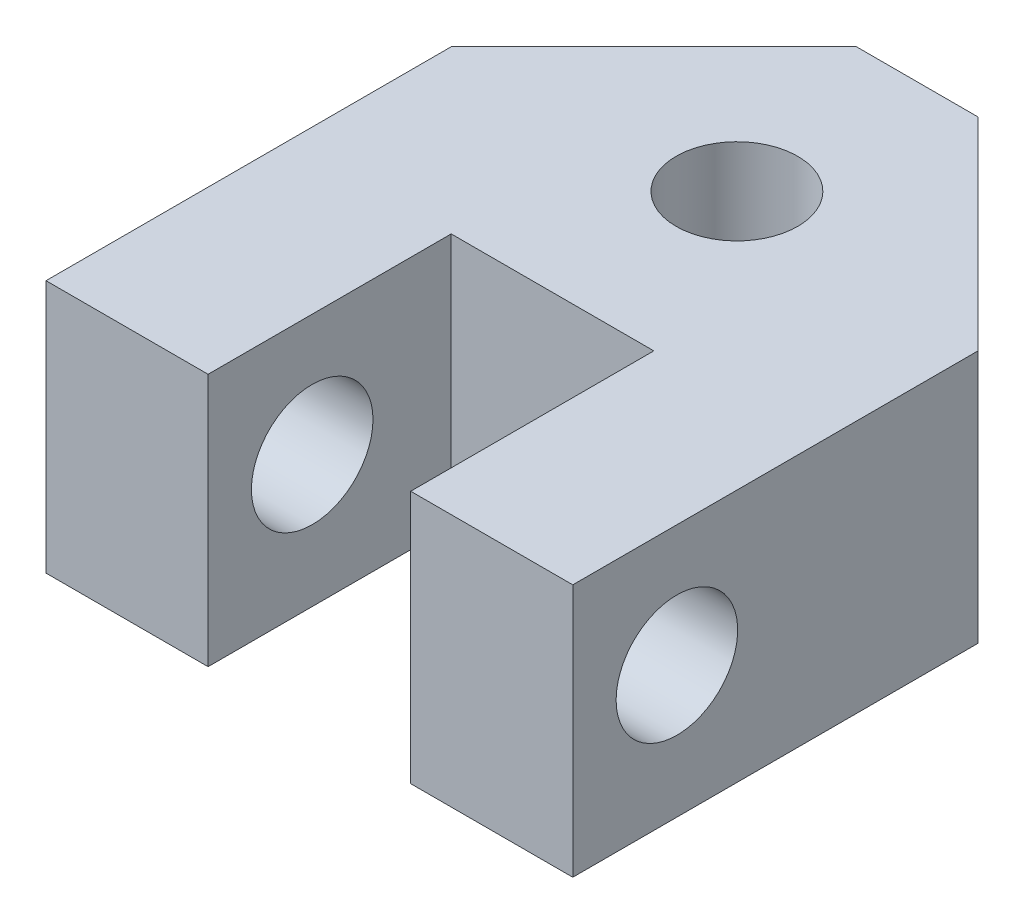
SolidWorks part; units mm, degrees
ref_plane "Спереди" through (0, 0, 0) normal (0, 0, 1) x (1, 0, 0)
ref_plane "Сверху" through (0, 0, 0) normal (0, 1, 0) x (1, 0, 0)
ref_plane "Справа" through (0, 0, 0) normal (1, 0, 0) x (0, 0, -1)
sketch "Эскиз1" plane through (0, 0, 0) normal (0, 0, 1) x (1, 0, 0)
  line L1 (-15, 6) -> (15, 6)
  line L2 (-15, 6) -> (-15, -7.5)
  line L3 (-15, -7.5) -> (15, -7.5)
  line L4 (15, 6) -> (15, -7.5)
extrude "Вытянуть1" add sketch "Эскиз1" along normal blind 20
sketch "Эскиз2" plane through (0, -7.5, 0) normal (0, -1, 0) x (1, 0, 0)
  line L0 (0, 21.5367) -> (0, 9.7512) construction
  line L2 (-15, 0) -> (15, 0) construction
  line L3 (-5, 28.1632) -> (5, 28.1632)
  line L4 (-5, 28.1632) -> (-5, 8)
  line L5 (-5, 8) -> (5, 8)
  line L6 (5, 28.1632) -> (5, 8)
  line L7 (-5, 28.1632) -> (5, 8) construction
  line L8 (-5, 8) -> (5, 28.1632) construction
  point P1 (0, 18.0816)
  dimension "D1" = 8
extrude "Вытянуть2" cut sketch "Эскиз2" against normal through all
sketch "Эскиз3" plane through (15, 0, 0) normal (1, 0, 0) x (0, 0, -1)
  circle A0 centre (-14.8614, 0) radius 3
extrude "Вытянуть3" cut sketch "Эскиз3" against normal through all
sketch "Эскиз6" plane through (0, 0, 0) normal (0, 0, -1) x (-1, 0, 0)
  line L0 (-15, 6) -> (15, 6) construction
  line L1 (15, 6) -> (-15, 6)
  line L2 (15, 6) -> (15, -7.5)
  line L3 (15, -7.5) -> (-15, -7.5)
  line L4 (-15, 6) -> (-15, -7.5)
extrude "Вытянуть5" add sketch "Эскиз6" along normal blind 10
sketch "Эскиз7" plane through (0, 6, 0) normal (0, 1, 0) x (1, 0, 0)
  circle A0 centre (0.2314, 0.8699) radius 3
extrude "Вырез-Вытянуть1" cut sketch "Эскиз7" against normal through all
sketch "Эскиз9" plane through (0, 6, 0) normal (0, 1, 0) x (1, 0, 0)
  line L0 (0, 10) -> (0, 20.7943) construction
  line L2 (-13, 15.424) -> (-13, -1.8651) construction
  line L3 (-15, -20) -> (-15, 10) construction
  line L4 (13, 13.3999) -> (13, -20.0583)
  line L5 (-19.524, 13.3999) -> (-13, 13.3999)
  line L6 (-19.524, 13.3999) -> (-19.524, -20.0583)
  line L7 (-19.524, -20.0583) -> (-13, -20.0583)
  line L8 (-13, 13.3999) -> (-13, -20.0583)
  line L9 (19.524, -20.0583) -> (13, -20.0583)
  line L10 (19.524, 13.3999) -> (19.524, -20.0583)
  line L11 (19.524, 13.3999) -> (13, 13.3999)
  dimension "D1" = 2
extrude "Вытянуть6" cut sketch "Эскиз9" against normal through all
sketch "Эскиз14" plane through (0, -7.5, 0) normal (0, -1, 0) x (1, 0, 0)
  line L1 (42.5138, 22.154) -> (-42.3901, 22.154)
  line L2 (42.5138, 22.154) -> (42.5138, -22.8093)
  line L3 (42.5138, -22.8093) -> (-42.3901, -22.8093)
  line L4 (-42.3901, 22.154) -> (-42.3901, -22.8093)
extrude "Вытянуть10" cut sketch "Эскиз14" against normal blind 1
chamfer "Chamfer1" distance 10 angle 45 2 edges at (13, -0.25, -10) (-13, -0.25, -10)
